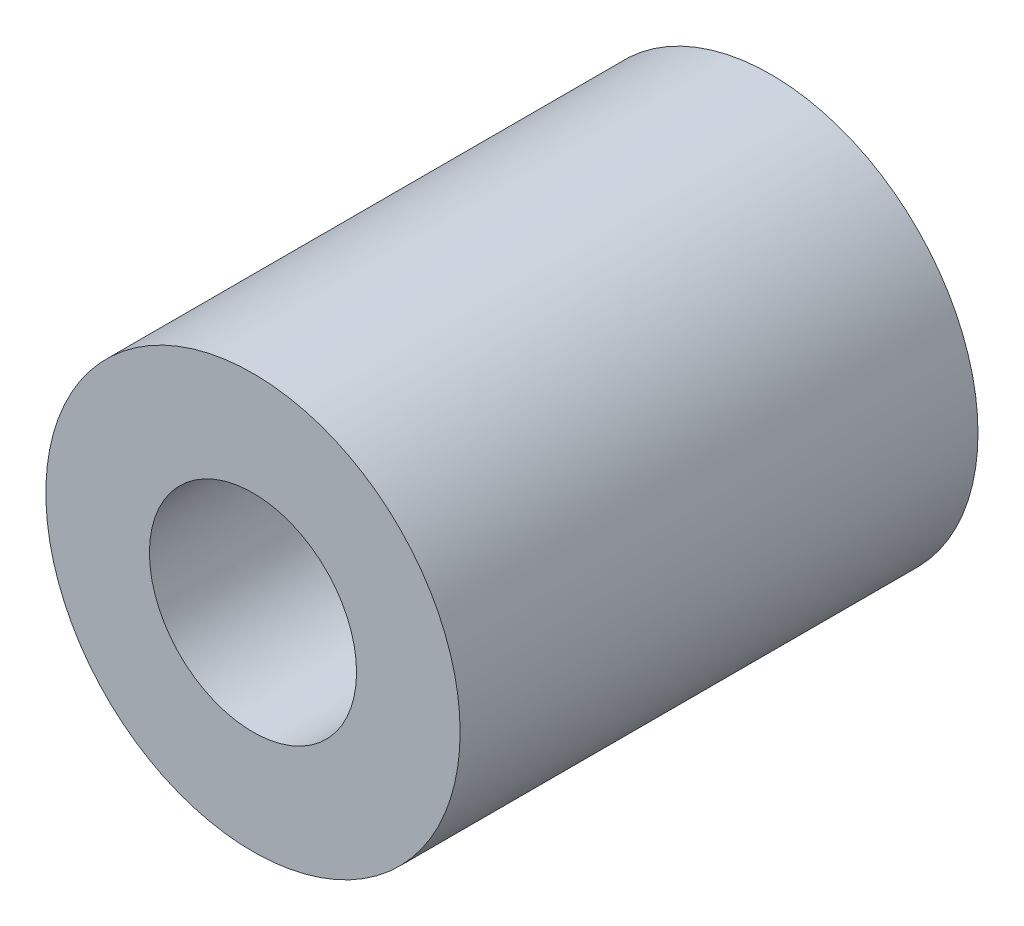
SolidWorks part; units mm, degrees
ref_plane "Front Plane" through (0, 0, 0) normal (0, 0, 1) x (1, 0, 0)
ref_plane "Top Plane" through (0, 0, 0) normal (0, 1, 0) x (1, 0, 0)
ref_plane "Right Plane" through (0, 0, 0) normal (1, 0, 0) x (0, 0, -1)
sketch "Sketch1" plane through (0, 0, 0) normal (0, 0, 1) x (1, 0, 0)
  circle A0 centre (0, 0) radius 8
  circle A1 centre (0, 0) radius 4
  dimension "D1" = 16
  dimension "D2" = 8
extrude "Boss-Extrude1" add sketch "Sketch1" along normal mid plane 20
